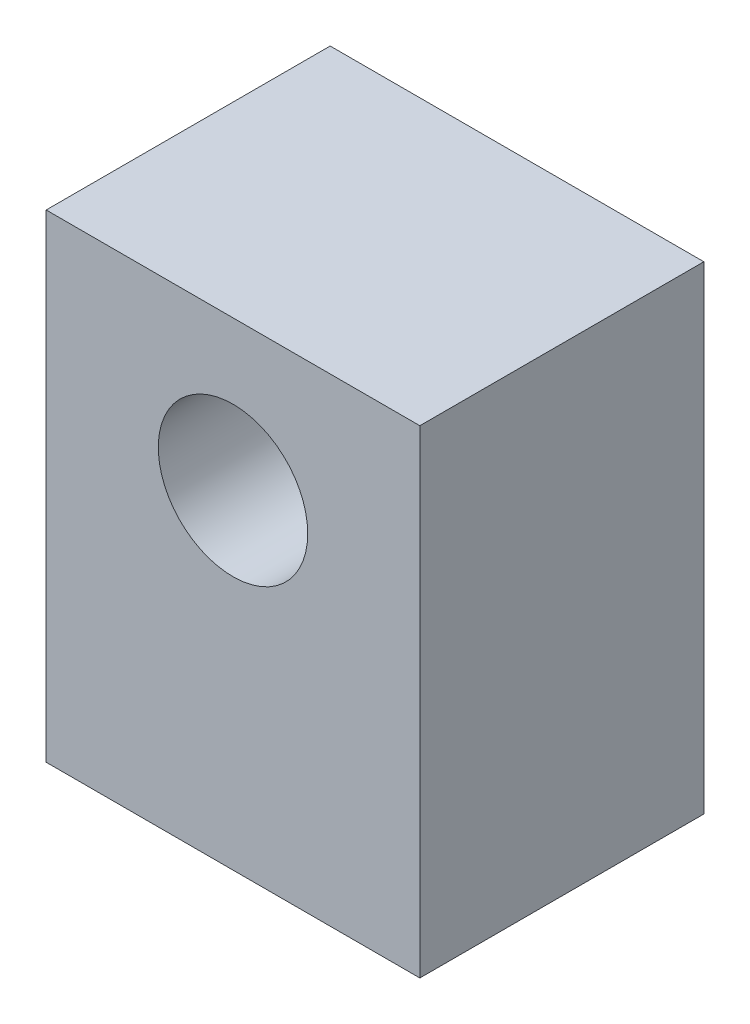
SolidWorks part; units mm, degrees
ref_plane "前基準面" through (0, 0, 0) normal (0, 0, 1) x (1, 0, 0)
ref_plane "上基準面" through (0, 0, 0) normal (0, 1, 0) x (1, 0, 0)
ref_plane "右基準面" through (0, 0, 0) normal (1, 0, 0) x (0, 0, -1)
sketch "草圖1" plane through (0, 0, 0) normal (0, 0, 1) x (1, 0, 0)
  line L1 (-6.25, -8) -> (6.25, -8)
  line L2 (-6.25, -8) -> (-6.25, 8)
  line L3 (-6.25, 8) -> (6.25, 8)
  line L4 (6.25, -8) -> (6.25, 8)
  line L5 (-6.25, -8) -> (6.25, 8) construction
  line L6 (-6.25, 8) -> (6.25, -8) construction
  point P0 (0, 0)
  dimension "D1" = 12.5
  dimension "D2" = 16
extrude "填料-伸長1" add sketch "草圖1" along normal blind 9.5
sketch "草圖2" plane through (0, 0, 9.5) normal (0, 0, 1) x (1, 0, 0)
  line L3 (6.25, 8) -> (-6.25, 8) construction
  circle A2 centre (0, 3) radius 2.5
  dimension "D1" = 5
  dimension "D2" = 5
extrude "除料-伸長1" cut sketch "草圖2" against normal up to vertex (9.5 mm away) up to point (0, 0, 0)
